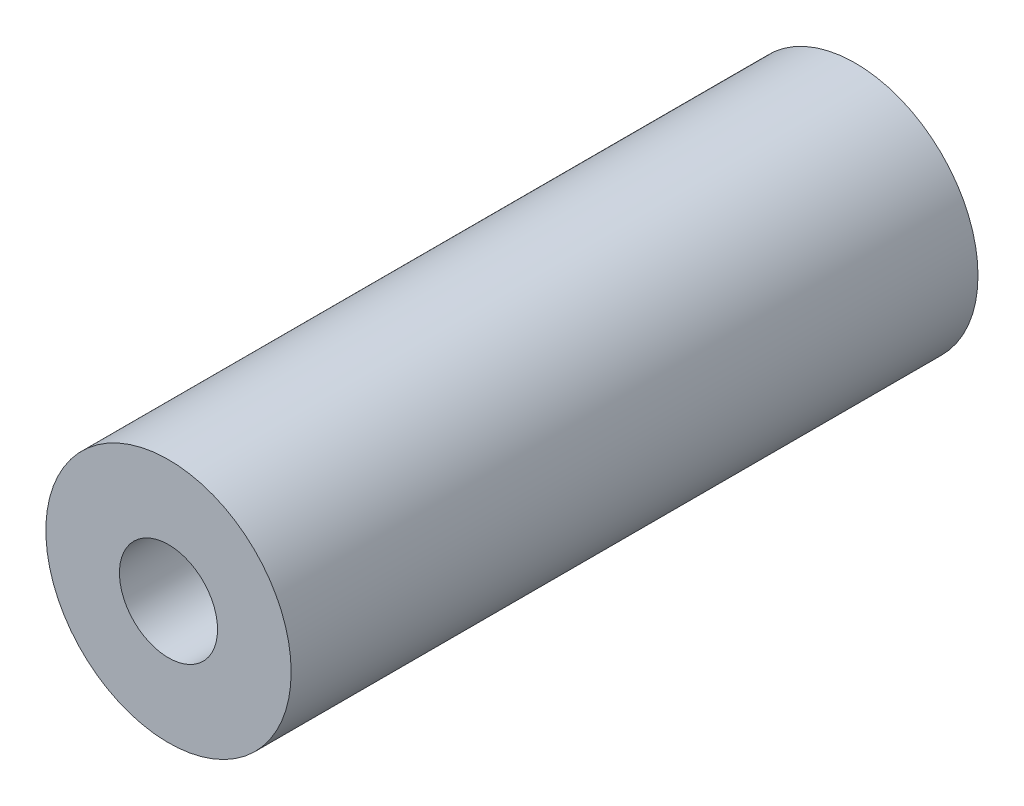
SolidWorks part; units mm, degrees
ref_plane "Front Plane" through (0, 0, 0) normal (0, 0, 1) x (1, 0, 0)
ref_plane "Top Plane" through (0, 0, 0) normal (0, 1, 0) x (1, 0, 0)
ref_plane "Right Plane" through (0, 0, 0) normal (1, 0, 0) x (0, 0, -1)
sketch "Sketch1" plane through (0, 0, 0) normal (0, 0, 1) x (1, 0, 0)
  circle A0 centre (24, 0) radius 2.5
  circle A1 centre (24, 0) radius 1
extrude "Boss-Extrude1" add sketch "Sketch1" along normal blind 14
cosmetic thread "Cosmetic Thread1"
